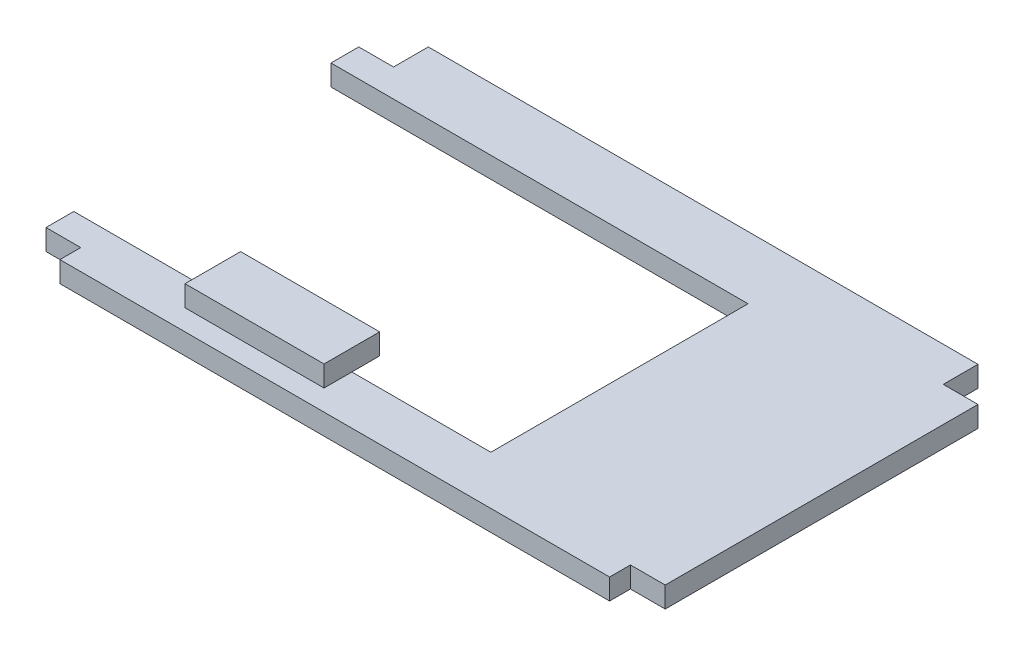
SolidWorks part; units mm, degrees
material "PVC rigido"
ref_plane "Piano frontale" through (0, 0, 0) normal (0, 0, 1) x (1, 0, 0)
ref_plane "Piano superiore" through (0, 0, 0) normal (0, 1, 0) x (1, 0, 0)
ref_plane "Piano destro" through (0, 0, 0) normal (1, 0, 0) x (0, 0, -1)
sketch "Schizzo1" plane through (0, 0, 0) normal (0, 0, 1) x (1, 0, 0)
  line L1 (80, -81) -> (159.0846, -81)
  line L2 (80, -81) -> (80, -84)
  line L3 (80, -84) -> (159.0846, -84)
  line L4 (159.0846, -81) -> (159.0846, -84)
extrude "Estrusione-Estrusione1" add sketch "Schizzo1" along normal up to surface (48 mm away) and the other way up to surface (5 mm away)
ref_plane "Piano" through (119.5423, 0, 0) normal (1, 0, 0) x (0, 0, -1)
sketch "Schizzo2" plane through (159.0846, 0, 0) normal (1, 0, 0) x (0, 0, -1)
  line L0 (0, -81) -> (0, -84) construction
  line L1 (0, -81) -> (-45, -81)
  line L2 (0, -81) -> (0, -84)
  line L3 (0, -84) -> (-45, -84)
  line L4 (-45, -81) -> (-45, -84)
  line L5 (-48, -84) -> (5, -84) construction
  line L6 (-48, -81) -> (5, -81) construction
extrude "Estrusione-Estrusione2" add sketch "Schizzo2" along normal blind 5
mirror "Specchia1" about plane through (119.5423, 0, 0) normal (1, 0, 0) of "Estrusione-Estrusione2"
sketch "Schizzo3" plane through (0, -81, 0) normal (0, 1, 0) x (1, 0, 0)
  line L0 (75, 0) -> (75, -45) construction
  line L1 (135, -41) -> (75, -41)
  line L2 (135, -41) -> (135, -4)
  line L3 (135, -4) -> (75, -4)
  line L4 (75, -41) -> (75, -4)
  line L7 (135, -22.5) -> (164.0846, -22.5) construction
  line L8 (164.0846, 0) -> (164.0846, -45) construction
  dimension "D1" = 60
  dimension "D2" = 37
extrude "Taglio-Estrusione1" cut sketch "Schizzo3" against normal blind 10
sketch "Schizzo4" plane through (0, -81, 0) normal (0, -1, 0) x (1, 0, 0)
  line L0 (105, 37) -> (105, 41) construction
  line L1 (95, 37) -> (115, 37)
  line L2 (95, 37) -> (95, 45)
  line L3 (95, 45) -> (115, 45)
  line L4 (115, 37) -> (115, 45)
  line L5 (75, 41) -> (135, 41) construction
  line L6 (115, 37) -> (135, 37) construction
  line L7 (135, 41) -> (135, 4) construction
  line L8 (75, 41) -> (75, 37) construction
  line L9 (75, 37) -> (95, 37) construction
  line L10 (105, 45) -> (105, 48) construction
  line L11 (159.0846, 48) -> (80, 48) construction
  line L12 (80, 48) -> (80, 45) construction
  dimension "D1" = 4
  dimension "D2" = 20
extrude "Estrusione-Estrusione3" add sketch "Schizzo4" against normal blind 3
move or copy body "Corpo-Sposta/copia1" [suppressed] bodies to move or copy 103
